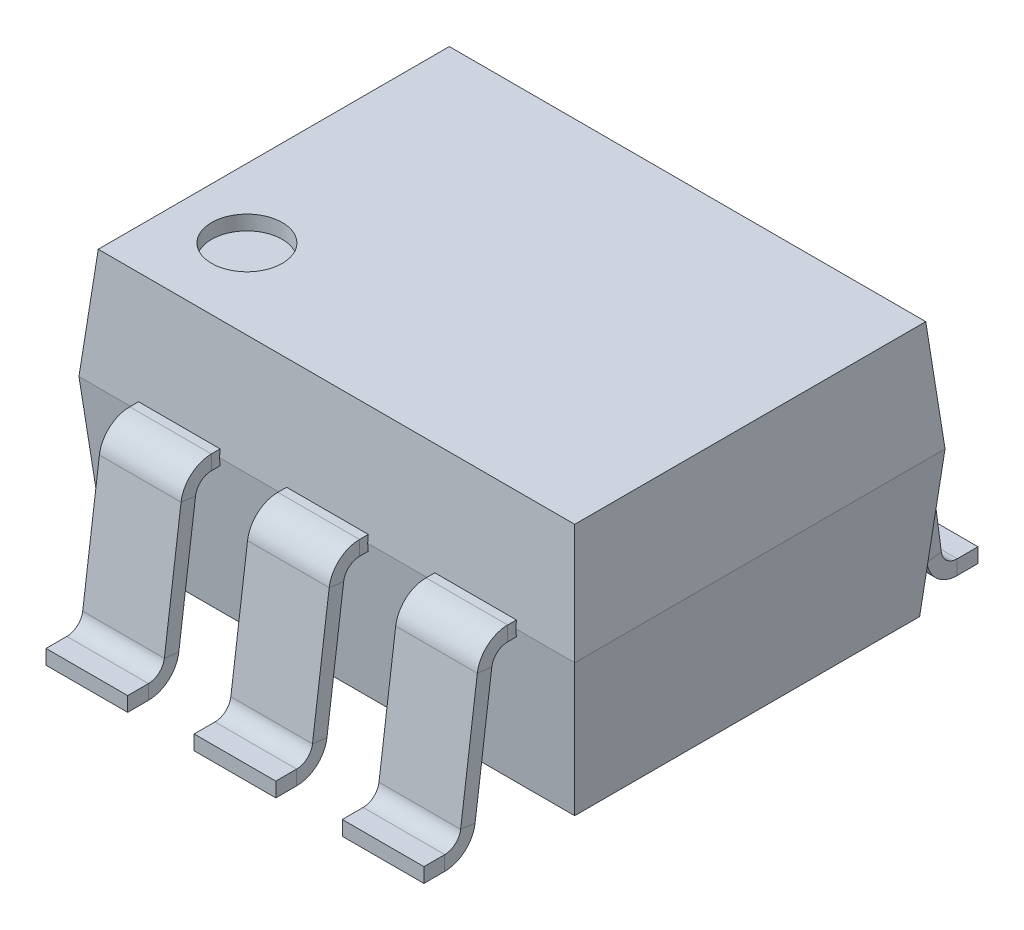
SolidWorks part; units mm, degrees
ref_plane "Front Plane" through (0, 0, 0) normal (0, 0, 1) x (1, 0, 0)
ref_plane "Top Plane" through (0, 0, 0) normal (0, 1, 0) x (1, 0, 0)
ref_plane "Right Plane" through (0, 0, 0) normal (1, 0, 0) x (0, 0, -1)
sketch "Sketch1" plane through (0, 0, 0) normal (0, 1, 0) x (1, 0, 0)
  line L1 (-4.25, -3.175) -> (4.25, -3.175)
  line L2 (-4.25, -3.175) -> (-4.25, 3.175)
  line L3 (-4.25, 3.175) -> (4.25, 3.175)
  line L4 (4.25, -3.175) -> (4.25, 3.175)
  line L5 (-4.25, -3.175) -> (4.25, 3.175) construction
  line L6 (-4.25, 3.175) -> (4.25, -3.175) construction
  point P0 (0, 0)
  dimension "D1" = 6.35
  dimension "D2" = 8.5
extrude "Boss-Extrude1" add sketch "Sketch1" along normal blind 1.89 draft 5 and the other way blind 2.49 draft 5
sketch "Sketch2" plane through (0, 0, 0) normal (0, 0, 1) x (1, 0, 0)
  line L1 (-0.7, 0.125) -> (0.7, 0.125)
  line L2 (-0.7, 0.125) -> (-0.7, -0.125)
  line L3 (-0.7, -0.125) -> (0.7, -0.125)
  line L4 (0.7, 0.125) -> (0.7, -0.125)
  line L5 (-0.7, 0.125) -> (0.7, -0.125) construction
  line L6 (-0.7, -0.125) -> (0.7, 0.125) construction
  point P0 (0, 0)
  dimension "D1" = 0.25
  dimension "D2" = 1.4
sketch "Sketch3" plane through (0, 0, 0) normal (1, 0, 0) x (0, 0, -1)
  line L0 (0, 0) -> (-3.314, 0)
  line L1 (-3.7106, -0.3478) -> (-3.9968, -2.5222)
  line L2 (-4.3934, -2.87) -> (-4.75, -2.87)
  line L3 (-3.314, 0) -> (-4.75, 0) construction
  line L4 (-4.75, 0) -> (-4.75, -2.87) construction
  arc A0 (-3.314, 0) -> (-3.7106, -0.3478) centre (-3.314, -0.4) ccw
  arc A1 (-3.9968, -2.5222) -> (-4.3934, -2.87) centre (-4.3934, -2.47) cw
  point P9 (-4.1597, -2.5498)
  dimension "D1" = 0.4
  dimension "D2" = 0.4
  dimension "D3" = 2.87
  dimension "D4" = 4.75
  dimension "D5" = 7.5
sweep "Sweep1" add profiles "Sketch2" path "Sketch3"
pattern_linear "LPattern1" count 2 spacing 2.54 along (1, 0, 0) count 2 spacing 2.54 along (-1, 0, 0) of "Sweep1"
mirror "Mirror1" about plane through (0, 0, 0) normal (0, 0, 1) of "LPattern1", "Sweep1"
sketch "Sketch4" plane through (0, 1.89, 0) normal (0, 1, 0) x (1, 0, 0)
  circle A0 centre (-2.9035, -1.6417) radius 0.6066
extrude "Cut-Extrude1" cut sketch "Sketch4" against normal blind 0.25
